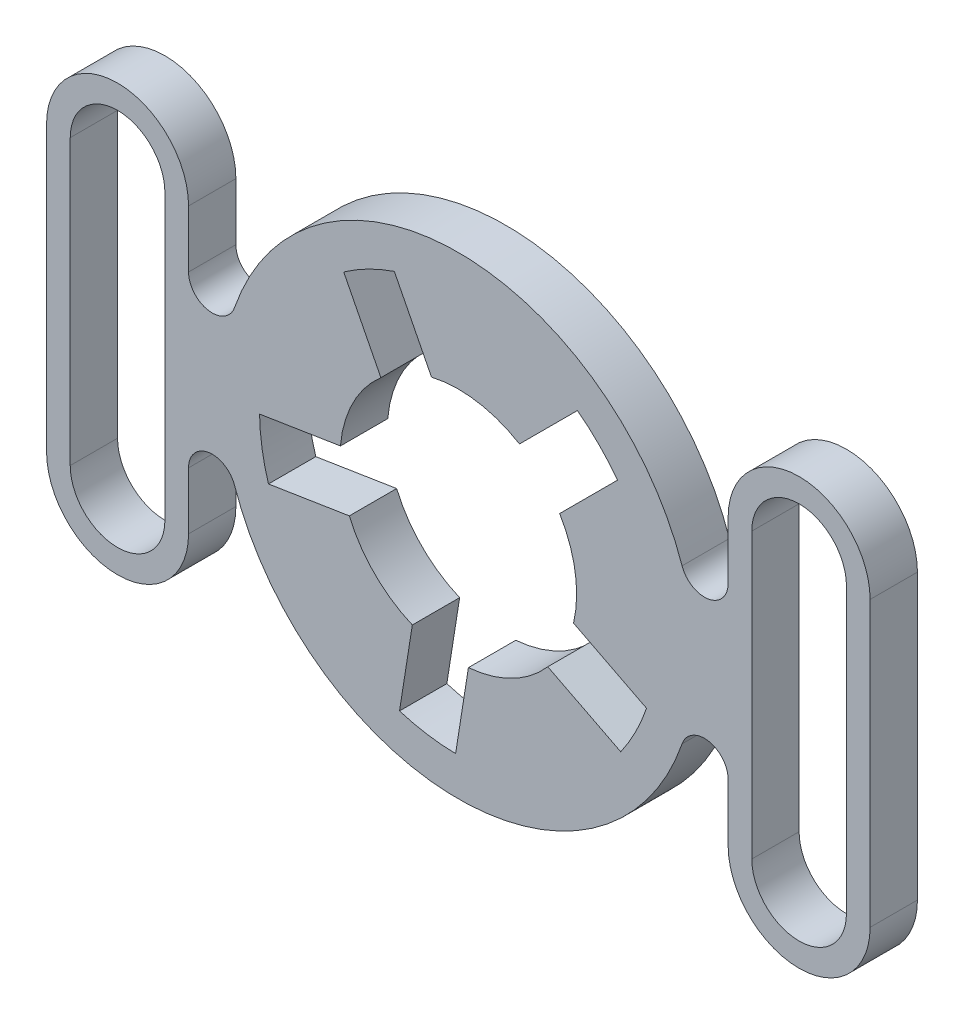
SolidWorks part; units mm, degrees
ref_plane "Front Plane" through (0, 0, 0) normal (0, 0, 1) x (1, 0, 0)
ref_plane "Top Plane" through (0, 0, 0) normal (0, 1, 0) x (1, 0, 0)
ref_plane "Right Plane" through (0, 0, 0) normal (1, 0, 0) x (0, 0, -1)
sketch "Sketch2" plane through (0, 0, 0) normal (0, 0, 1) x (1, 0, 0)
  line L0 (-72, -30) -> (-72, 30) construction
  line L1 (-82, -30) -> (-82, 30)
  line L2 (-62, -30) -> (-62, 30)
  line L3 (-87, -30) -> (-87, 30)
  line L4 (-57, -30) -> (-57, -17.9165)
  line L5 (-126.0436, 0) -> (151.3663, 0) construction
  line L6 (-57, 17.9165) -> (-57, 30)
  line L7 (24.3481, -5.672) -> (39.7624, -13.526)
  line L8 (-57, -30) -> (-57, 30) construction
  line L9 (12.9184, 21.4036) -> (25.1512, 33.6365)
  line L10 (0, 0) -> (29.6985, 29.6985) construction
  line L11 (21.4036, 12.9184) -> (33.6365, 25.1512)
  line L12 (-4.2426, 4.2426) -> (25.4558, 33.9411) construction
  line L13 (18.9002, -16.3641) -> (34.3145, -24.2181)
  line L14 (2.1296, -24.9091) -> (-0.5767, -41.996)
  line L15 (-9.7227, -23.0319) -> (-12.429, -40.1188)
  line L16 (-23.0319, -9.7227) -> (-40.1188, -12.429)
  line L17 (-24.9091, 2.1296) -> (-41.996, -0.5767)
  line L18 (-16.3641, 18.9002) -> (-24.2181, 34.3145)
  line L19 (-5.672, 24.3481) -> (-13.526, 39.7624)
  line L20 (0, 78.8126) -> (0, -97.1283) construction
  line L21 (57, 17.9165) -> (57, 30)
  line L22 (57, -30) -> (57, -17.9165)
  line L23 (87, -30) -> (87, 30)
  line L24 (72, -30) -> (72, 30) construction
  line L25 (82, -30) -> (82, 30)
  line L26 (62, -30) -> (62, 30)
  circle A0 centre (0, 0) radius 15
  arc A1 (12.9184, 21.4036) -> (-5.672, 24.3481) centre (0, 0) ccw
  circle A2 centre (0, 0) radius 42 construction
  arc A3 (-47.2727, -16.2877) -> (47.2727, -16.2877) centre (0, 0) ccw
  arc A4 (-82, -30) -> (-62, -30) centre (-72, -30) ccw
  arc A5 (-62, 30) -> (-82, 30) centre (-72, 30) ccw
  arc A6 (-57, 30) -> (-87, 30) centre (-72, 30) ccw
  arc A7 (-87, -30) -> (-57, -30) centre (-72, -30) ccw
  arc A8 (-57, -17.9165) -> (-47.2727, -16.2877) centre (-52, -17.9165) cw
  arc A9 (-57, 17.9165) -> (-47.2727, 16.2877) centre (-52, 17.9165) ccw
  arc A10 (25.1512, 33.6365) -> (33.6365, 25.1512) centre (0, 0) cw
  arc A11 (39.7624, -13.526) -> (34.3145, -24.2181) centre (0, 0) cw
  arc A12 (-0.5767, -41.996) -> (-12.429, -40.1188) centre (0, 0) cw
  arc A13 (-40.1188, -12.429) -> (-41.996, -0.5767) centre (0, 0) cw
  arc A14 (-24.2181, 34.3145) -> (-13.526, 39.7624) centre (0, 0) cw
  arc A15 (-16.3641, 18.9002) -> (-24.9091, 2.1296) centre (0, 0) ccw
  arc A16 (-23.0319, -9.7227) -> (-9.7227, -23.0319) centre (0, 0) ccw
  arc A17 (2.1296, -24.9091) -> (18.9002, -16.3641) centre (0, 0) ccw
  arc A18 (24.3481, -5.672) -> (21.4036, 12.9184) centre (0, 0) ccw
  arc A19 (57, -17.9165) -> (47.2727, -16.2877) centre (52, -17.9165) ccw
  arc A20 (57, 17.9165) -> (47.2727, 16.2877) centre (52, 17.9165) cw
  arc A21 (87, -30) -> (57, -30) centre (72, -30) cw
  arc A22 (57, 30) -> (87, 30) centre (72, 30) cw
  arc A23 (82, -30) -> (62, -30) centre (72, -30) cw
  arc A24 (62, 30) -> (82, 30) centre (72, 30) cw
  arc A25 (47.2727, 16.2877) -> (-47.2727, 16.2877) centre (0, 0) ccw
  point P5 (4.2426, -4.2426)
  point P8 (-72, 0)
  point P27 (33.9411, 25.4558)
  point P55 (0, 0)
  point P61 (72, 0)
  dimension "D1" = 30
  dimension "D2" = 50
  dimension "D3" = 84
  dimension "D4" = 100
  dimension "D6" = 10
  dimension "D9" = 5
  dimension "D13" = 5
  dimension "D5" = 60
  dimension "D7" = 72
  dimension "D10" = 45
  dimension "D11" = 6
  dimension "D8" = 5
  dimension "D12" = 6
extrude "Boss-Extrude1" add sketch "Sketch2" along normal mid plane 10 contours A20 A25 A9 L6 A6 L3 A7 L4 A8 A3 A19 L22 A21 L23 A22 L21 L26 A24 L25 A23 A5 L2 A4 L1 A18 L7 A11 L13 A17 L14 A12 L15 A16 L16 A13 L17 A15 L18 A14 L19 A1 L9 A10 L11
